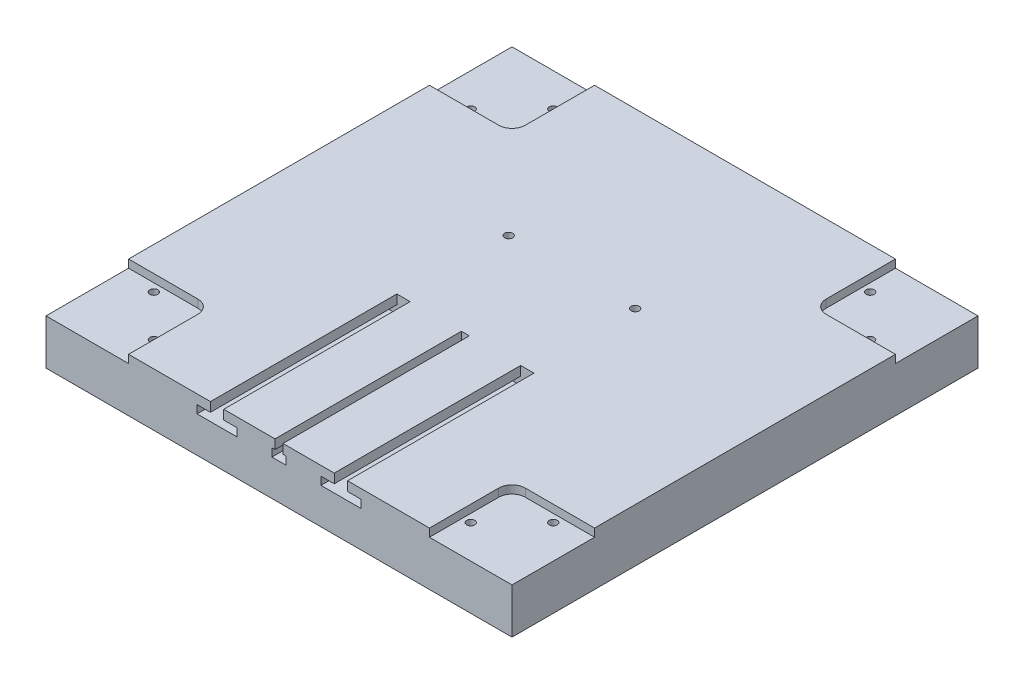
SolidWorks part; units mm, degrees
ref_plane "Front Plane" through (0, 0, 0) normal (0, 0, 1) x (1, 0, 0)
ref_plane "Top Plane" through (0, 0, 0) normal (0, 1, 0) x (1, 0, 0)
ref_plane "Right Plane" through (0, 0, 0) normal (1, 0, 0) x (0, 0, -1)
sketch "Sketch1" plane through (0, 0, 0) normal (0, 1, 0) x (1, 0, 0)
  line L0 (0, 87.5) -> (0, -87.5) construction
  line L1 (-87.5, 87.5) -> (87.5, 87.5)
  line L2 (-87.5, 87.5) -> (-87.5, -87.5)
  line L3 (-87.5, -87.5) -> (87.5, -87.5)
  line L4 (87.5, 87.5) -> (87.5, -87.5)
  line L5 (-87.5, 87.5) -> (87.5, -87.5) construction
  line L6 (-87.5, -87.5) -> (87.5, 87.5) construction
  line L15 (-87.5, 0) -> (87.5, 0) construction
  point P0 (0, 0)
  dimension "D1" = 175
  dimension "D2" = 175
extrude "Boss-Extrude2" add sketch "Sketch1" along normal blind 20
sketch "Sketch7" plane through (0, 20, 0) normal (0, 1, 0) x (1, 0, 0)
  line L0 (0, 87.5) -> (0, -87.5) construction
  line L1 (-87.5, 87.5) -> (-56.5, 87.5)
  line L2 (-87.5, 87.5) -> (-87.5, 56.5)
  line L3 (-87.5, 56.5) -> (-61.5, 56.5)
  line L4 (-56.5, 87.5) -> (-56.5, 61.5)
  line L5 (87.5, 87.5) -> (-87.5, 87.5) construction
  line L6 (-87.5, -87.5) -> (87.5, -87.5) construction
  line L7 (-87.5, 0) -> (87.5, 0) construction
  line L8 (-87.5, 87.5) -> (-87.5, -87.5) construction
  line L9 (87.5, -87.5) -> (87.5, 87.5) construction
  line L10 (87.5, 56.5) -> (61.5, 56.5)
  line L11 (56.5, 87.5) -> (56.5, 61.5)
  line L12 (87.5, 87.5) -> (56.5, 87.5)
  line L13 (87.5, 87.5) -> (87.5, 56.5)
  line L14 (87.5, -87.5) -> (87.5, -56.5)
  line L15 (87.5, -87.5) -> (56.5, -87.5)
  line L16 (56.5, -87.5) -> (56.5, -61.5)
  line L17 (87.5, -56.5) -> (61.5, -56.5)
  line L18 (-56.5, -87.5) -> (-56.5, -61.5)
  line L19 (-87.5, -56.5) -> (-61.5, -56.5)
  line L20 (-87.5, -87.5) -> (-87.5, -56.5)
  line L21 (-87.5, -87.5) -> (-56.5, -87.5)
  arc A0 (-61.5, 56.5) -> (-56.5, 61.5) centre (-61.5, 61.5) ccw
  arc A1 (61.5, 56.5) -> (56.5, 61.5) centre (61.5, 61.5) cw
  arc A2 (61.5, -56.5) -> (56.5, -61.5) centre (61.5, -61.5) ccw
  arc A3 (-61.5, -56.5) -> (-56.5, -61.5) centre (-61.5, -61.5) cw
  point P7 (-56.5, 56.5)
  point P38 (-56.5, -56.5)
  dimension "D3" = 5
  dimension "D1" = 31
  dimension "D2" = 31
extrude "Cut-Extrude6" cut sketch "Sketch7" against normal blind 3
sketch "Sketch8" plane through (0, 17, 0) normal (0, 1, 0) x (1, 0, 0)
  line L0 (-75, -62.5) -> (-75, -56.5) construction
  line L5 (-61.5, -56.5) -> (-87.5, -56.5) construction
  line L6 (-62.5, -75) -> (-56.5, -75) construction
  line L7 (-56.5, -87.5) -> (-56.5, -61.5) construction
  line L8 (-87.5, -87.5) -> (-56.5, -87.5) construction
  line L9 (-87.5, -56.5) -> (-87.5, -87.5) construction
  line L10 (0, 87.5) -> (0, -87.5) construction
  line L11 (56.5, 87.5) -> (-56.5, 87.5) construction
  line L12 (-56.5, -87.5) -> (56.5, -87.5) construction
  line L13 (62.5, -75) -> (56.5, -75) construction
  line L14 (75, -62.5) -> (75, -56.5) construction
  line L15 (-87.5, 0) -> (87.5, 0) construction
  line L16 (-87.5, 56.5) -> (-87.5, -56.5) construction
  line L17 (87.5, -56.5) -> (87.5, 56.5) construction
  circle A0 centre (-75, -59.5) radius 1.5
  circle A1 centre (-59.5, -75) radius 1.5
  circle A2 centre (59.5, -75) radius 1.5
  circle A3 centre (75, -59.5) radius 1.5
  circle A4 centre (59.5, 75) radius 1.5
  circle A5 centre (75, 59.5) radius 1.5
  circle A6 centre (-59.5, 75) radius 1.5
  circle A7 centre (-75, 59.5) radius 1.5
  dimension "D3" = 3
  dimension "D4" = 3
  dimension "D1" = 28
  dimension "D2" = 28
  dimension "D5" = 12.5
  dimension "D6" = 12.5
extrude "Cut-Extrude7" cut sketch "Sketch8" against normal up to next
sketch "Sketch9" plane through (0, 0, 87.5) normal (0, 0, 1) x (1, 0, 0)
  line L0 (0, 20) -> (0, 0) construction
  line L1 (-56.5, 20) -> (56.5, 20) construction
  line L2 (0, 10) -> (-46.5, 10) construction
  line L3 (-46.5, 20) -> (46.5, 20)
  line L4 (-46.5, 20) -> (-46.5, 0)
  line L5 (-46.5, 0) -> (46.5, 0)
  line L6 (46.5, 20) -> (46.5, 0)
  line L7 (-46.5, 20) -> (46.5, 0) construction
  line L8 (-46.5, 0) -> (46.5, 20) construction
  line L9 (-46.5, 10) -> (0, 10) construction
  line L10 (-20.75, 16.5) -> (-15.75, 16.5)
  line L11 (-23.25, 10) -> (-23.25, 20) construction
  line L12 (-30.75, 16.5) -> (-25.75, 16.5)
  line L13 (-30.75, 16.5) -> (-30.75, 13.5)
  line L14 (-30.75, 13.5) -> (-15.75, 13.5)
  line L15 (-15.75, 16.5) -> (-15.75, 13.5)
  line L16 (-30.75, 16.5) -> (-15.75, 13.5) construction
  line L17 (-30.75, 13.5) -> (-15.75, 16.5) construction
  line L18 (-25.75, 20) -> (-20.75, 20)
  line L19 (-25.75, 20) -> (-25.75, 16.5)
  line L21 (-20.75, 20) -> (-20.75, 16.5)
  line L22 (-25.75, 20) -> (-20.75, 16.5) construction
  line L23 (-25.75, 16.5) -> (-20.75, 20) construction
  line L24 (25.75, 16.5) -> (20.75, 20) construction
  line L25 (25.75, 20) -> (20.75, 16.5) construction
  line L26 (30.75, 13.5) -> (15.75, 16.5) construction
  line L27 (30.75, 16.5) -> (15.75, 13.5) construction
  line L28 (20.75, 20) -> (20.75, 16.5)
  line L29 (25.75, 20) -> (25.75, 16.5)
  line L30 (25.75, 20) -> (20.75, 20)
  line L31 (15.75, 16.5) -> (15.75, 13.5)
  line L32 (30.75, 13.5) -> (15.75, 13.5)
  line L33 (30.75, 16.5) -> (30.75, 13.5)
  line L34 (30.75, 16.5) -> (25.75, 16.5)
  line L35 (20.75, 16.5) -> (15.75, 16.5)
  line L36 (-15.75, 15) -> (15.75, 15) construction
  line L37 (1.5, 16.5) -> (2.65, 16.5)
  line L38 (-2.65, 16.5) -> (-1.5, 16.5)
  line L39 (-2.65, 16.5) -> (-2.65, 13.5)
  line L40 (-2.65, 13.5) -> (2.65, 13.5)
  line L41 (2.65, 16.5) -> (2.65, 13.5)
  line L42 (-2.65, 16.5) -> (2.65, 13.5) construction
  line L43 (-2.65, 13.5) -> (2.65, 16.5) construction
  line L44 (-1.5, 20) -> (1.5, 20)
  line L45 (-1.5, 20) -> (-1.5, 16.5)
  line L47 (1.5, 20) -> (1.5, 16.5)
  line L48 (-1.5, 20) -> (1.5, 16.5) construction
  line L49 (-1.5, 16.5) -> (1.5, 20) construction
  point P5 (0, 10)
  point P13 (-23.25, 15)
  point P19 (-23.25, 18.25)
  point P32 (23.25, 18.25)
  point P33 (23.25, 15)
  point P36 (0, 15)
  point P41 (0, 18.25)
  dimension "D1" = 93
  dimension "D2" = 20
  dimension "D3" = 3
  dimension "D4" = 15
  dimension "D5" = 3.5
  dimension "D6" = 5
  dimension "D7" = 5.3
  dimension "D8" = 3
  dimension "D9" = 3.5
  dimension "D10" = 3
  dimension "D11" = 46.5
extrude "Cut-Extrude8" cut sketch "Sketch9" against normal blind 70 contours L21 L3 L19 L12 L13 L14 L15 L10 | L28 L35 L31 L32 L33 L34 L29 L3 | L38 L45 L44 L47 L37 L41 L40 L39
sketch "Sketch10" plane through (0, 20, 0) normal (0, 1, 0) x (1, 0, 0)
  line L0 (56.5, 87.5) -> (-56.5, 87.5) construction
  line L1 (-23.75, 22.5) -> (23.75, 22.5) construction
  line L3 (87.5, -56.5) -> (87.5, 56.5) construction
  circle A0 centre (-23.75, 22.5) radius 1.5
  circle A1 centre (23.75, 22.5) radius 1.5
  point P2 (0, 87.5)
  point P3 (0, 22.5)
  point P7 (0, 32.5)
  dimension "D1" = 3
  dimension "D2" = 3
  dimension "D3" = 47.5
  dimension "D4" = 55
  dimension "D5" = 87.5
extrude "Cut-Extrude9" cut sketch "Sketch10" against normal up to next
